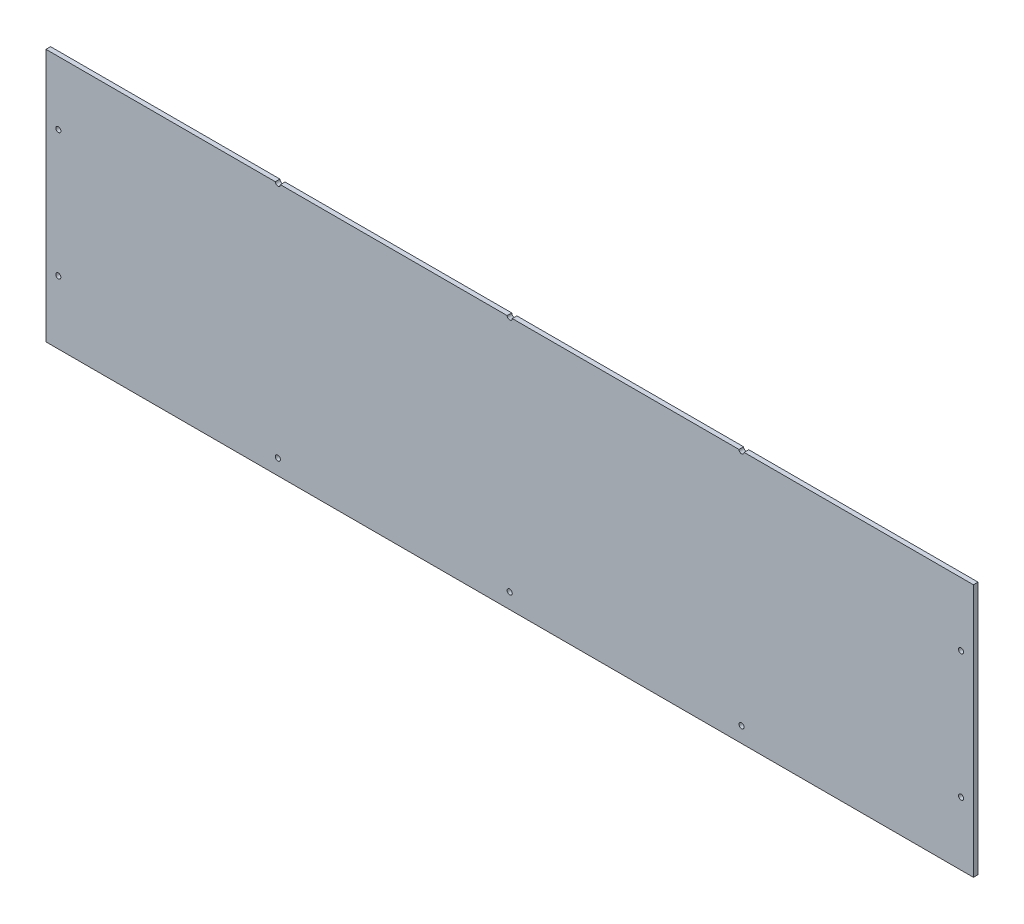
SolidWorks part; units mm, degrees
ref_plane "Front Plane" through (0, 0, 0) normal (0, 0, 1) x (1, 0, 0)
ref_plane "Top Plane" through (0, 0, 0) normal (0, 1, 0) x (1, 0, 0)
ref_plane "Right Plane" through (0, 0, 0) normal (1, 0, 0) x (0, 0, -1)
sketch "Sketch1" plane through (0, 0, 0) normal (0, 0, 1) x (1, 0, 0)
  line L2 (-452, 123.5) -> (-452, -123.5)
  line L4 (452, 123.5) -> (452, -123.5)
  line L10 (-452, -123.5) -> (452, -123.5)
  line L11 (0, -123.5) -> (0, 123.5) construction
  line L16 (-452, 0) -> (452, 0) construction
  line L25 (-452, 123.5) -> (-228.5, 123.5)
  line L26 (-223.5, 123.5) -> (-2.5, 123.5)
  line L27 (228.5, 123.5) -> (452, 123.5)
  line L28 (2.5, 123.5) -> (223.5, 123.5)
  arc A3 (-2.5, 123.5) -> (2.5, 123.5) centre (0, 123.5) ccw
  circle A8 centre (-440, 61.75) radius 2.5
  circle A9 centre (-440, -61.75) radius 2.5
  circle A10 centre (440, -61.75) radius 2.5
  circle A12 centre (440, 61.75) radius 2.5
  circle A15 centre (0, -108.5) radius 2.5
  circle A27 centre (226, -108.5) radius 2.5
  circle A28 centre (-226, -108.5) radius 2.5
  arc A29 (223.5, 123.5) -> (228.5, 123.5) centre (226, 123.5) ccw
  arc A30 (-228.5, 123.5) -> (-223.5, 123.5) centre (-226, 123.5) ccw
  point P18 (-452, 123.5)
  dimension "D5" = 2
  dimension "D3" = 5
  dimension "D1" = 247
  dimension "D2" = 904
  dimension "D4" = 452
  dimension "D6" = 2
extrude "Boss-Extrude1" add sketch "Sketch1" along normal blind 4.5
